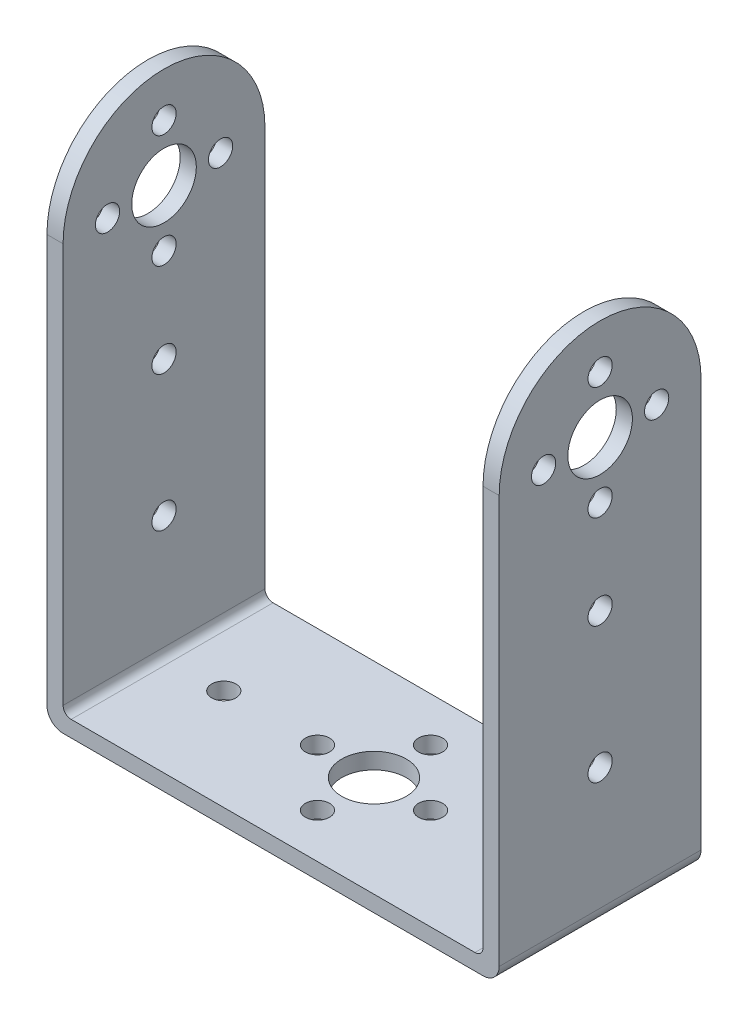
SolidWorks part; units mm, degrees
ref_plane "前视基准面" through (0, 0, 0) normal (0, 0, 1) x (1, 0, 0)
ref_plane "上视基准面" through (0, 0, 0) normal (0, 1, 0) x (1, 0, 0)
ref_plane "右视基准面" through (0, 0, 0) normal (1, 0, 0) x (0, 0, -1)
ref_plane "基准面4" through (56, 0, 0) normal (1, 0, 0) x (0, 0, -1)
sketch "草图1" plane through (56, 0, 0) normal (1, 0, 0) x (0, 0, -1)
  line L0 (-25, 50) -> (-25, -2.5)
  line L1 (-25, -2.5) -> (0, -2.5)
  line L2 (0, -2.5) -> (0, 50)
  arc A0 (0, 50) -> (-25, 50) centre (-12.5, 50) ccw
extrude "凸台-拉伸1" add sketch "草图1" against normal blind 56
sketch "草图2" plane through (0, 0, 25) normal (0, 0, 1) x (1, 0, 0)
  line L0 (2, 99.5) -> (2, -0.5)
  line L1 (2, -0.5) -> (54, -0.5)
  line L2 (54, -0.5) -> (54, 99.5)
  line L3 (54, 99.5) -> (2, 99.5)
  dimension "D1" = 100
extrude "切除-拉伸1" cut sketch "草图2" against normal through all
hole_wizard "Ø8.0 (8) 直径孔1" positions "草图4" profile "草图3" hole size "Ø8.0" standard "ANSI Metric"
sketch "草图4" plane through (56, 0, 0) normal (1, 0, 0) x (0, 0, -1)
  point P0 (-12.5, 50)
sketch "草图3" plane through (56, 50, 12.5) normal (0, 1, 0) x (0, 0, -1)
  line L0 (0, 0) -> (0, 2)
  line L1 (0, 2) -> (4, 2)
  line L2 (4, 2) -> (4, 0)
  line L5 (4, 0) -> (0, 0)
  line L11 (0, -6.35) -> (0, 107.95) construction
  dimension "通孔孔直径" = 8
  dimension "通孔孔深度" = 2
hole_wizard "Ø8.0 (8) 直径孔2" positions "草图6" profile "草图5" hole size "Ø8.0" standard "ANSI Metric"
sketch "草图6" plane through (2, 0, 0) normal (1, 0, 0) x (0, 0, -1)
  point P0 (-12.5, 50)
sketch "草图5" plane through (2, 50, 12.5) normal (0, 1, 0) x (0, 0, -1)
  line L0 (0, 0) -> (0, 2)
  line L1 (0, 2) -> (4, 2)
  line L2 (4, 2) -> (4, 0)
  line L5 (4, 0) -> (0, 0)
  line L11 (0, -6.35) -> (0, 107.95) construction
  dimension "通孔孔直径" = 8
  dimension "通孔孔深度" = 2
hole_wizard "Ø3.0 (3) 直径孔1" positions "草图8" profile "草图7" hole size "Ø3.0" standard "ANSI Metric"
sketch "草图8" plane through (56, 0, 0) normal (1, 0, 0) x (0, 0, -1)
  point P0 (-5.5, 50)
  point P1 (-12.5, 57)
  point P2 (-12.5, 31.4)
  point P3 (-12.5, 43)
  point P4 (-19.5, 50)
  point P5 (-12.5, 14.6)
sketch "草图7" plane through (56, 50, 5.5) normal (0, 1, 0) x (0, 0, -1)
  line L0 (0, 0) -> (0, 2)
  line L1 (0, 2) -> (1.5, 2)
  line L2 (1.5, 2) -> (1.5, 0)
  line L5 (1.5, 0) -> (0, 0)
  line L11 (0, -6.35) -> (0, 107.95) construction
  dimension "通孔孔直径" = 3
  dimension "通孔孔深度" = 2
hole_wizard "Ø3.0 (3) 直径孔2" positions "草图10" profile "草图9" hole size "Ø3.0" standard "ANSI Metric"
sketch "草图10" plane through (2, 0, 0) normal (1, 0, 0) x (0, 0, -1)
  point P0 (-5.5, 50)
  point P1 (-12.5, 57)
  point P2 (-12.5, 31.4)
  point P3 (-12.5, 43)
  point P4 (-19.5, 50)
  point P5 (-12.5, 14.6)
sketch "草图9" plane through (2, 50, 5.5) normal (0, 1, 0) x (0, 0, -1)
  line L0 (0, 0) -> (0, 2)
  line L1 (0, 2) -> (1.5, 2)
  line L2 (1.5, 2) -> (1.5, 0)
  line L5 (1.5, 0) -> (0, 0)
  line L11 (0, -6.35) -> (0, 107.95) construction
  dimension "通孔孔直径" = 3
  dimension "通孔孔深度" = 2
hole_wizard "Ø3.0 (3) 直径孔3" positions "草图12" profile "草图11" hole size "Ø3.0" standard "ANSI Metric"
sketch "草图12" plane through (0, -2.5, 0) normal (0, -1, 0) x (-1, 0, 0)
  point P0 (-46.6, -12.5)
  point P1 (-21, -12.5)
  point P2 (-35, -12.5)
  point P3 (-9.4, -12.5)
  point P4 (-28, -19.5)
  point P5 (-28, -5.5)
sketch "草图11" plane through (46.6, -2.5, 12.5) normal (1, 0, 0) x (0, 0, -1)
  line L0 (0, 0) -> (0, 2)
  line L1 (0, 2) -> (1.5, 2)
  line L2 (1.5, 2) -> (1.5, 0)
  line L5 (1.5, 0) -> (0, 0)
  line L11 (0, -6.35) -> (0, 107.95) construction
  dimension "通孔孔直径" = 3
  dimension "通孔孔深度" = 2
hole_wizard "Ø8.0 (8) 直径孔3" positions "草图14" profile "草图13" hole size "Ø8.0" standard "ANSI Metric"
sketch "草图14" plane through (0, -2.5, 0) normal (0, -1, 0) x (-1, 0, 0)
  point P0 (-28, -12.5)
sketch "草图13" plane through (28, -2.5, 12.5) normal (1, 0, 0) x (0, 0, -1)
  line L0 (0, 0) -> (0, 2)
  line L1 (0, 2) -> (4, 2)
  line L2 (4, 2) -> (4, 0)
  line L5 (4, 0) -> (0, 0)
  line L11 (0, -6.35) -> (0, 107.95) construction
  dimension "通孔孔直径" = 8
  dimension "通孔孔深度" = 2
fillet "圆角1" radius 1 2 edges at (2, -0.5, 12.5) (54, -0.5, 12.5)
fillet "圆角2" radius 2 2 edges at (0, -2.5, 12.5) (56, -2.5, 12.5)
ref_plane "Mid Plane" through (28, 0, 0) normal (-1, 0, 0) x (0, 0, 1)
ref_plane "Plane2" through (0, 0, 12.5) normal (0, 0, 1) x (1, 0, 0)
